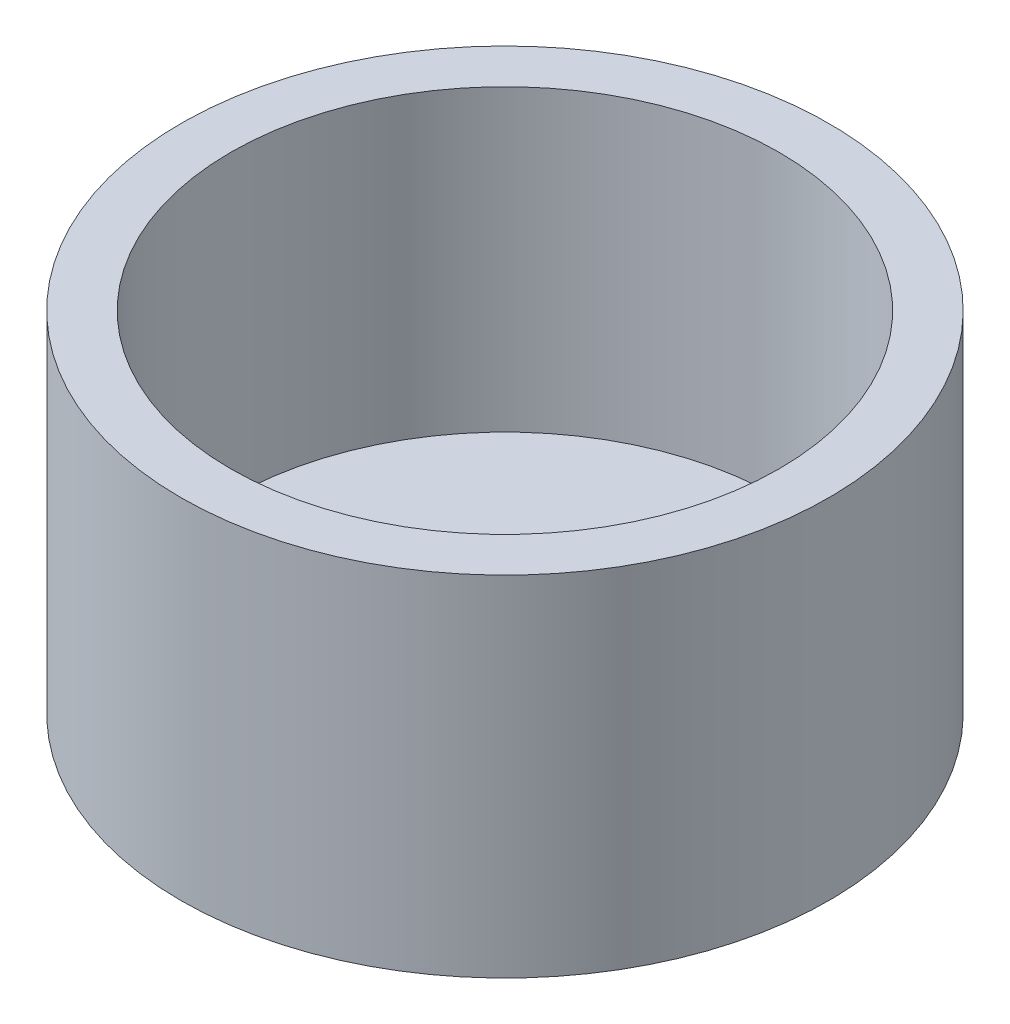
SolidWorks part; units mm, degrees
material "Polyether Polyol"
ref_plane "Front Plane" through (0, 0, 0) normal (0, 0, 1) x (1, 0, 0)
ref_plane "Top Plane" through (0, 0, 0) normal (0, 1, 0) x (1, 0, 0)
ref_plane "Right Plane" through (0, 0, 0) normal (1, 0, 0) x (0, 0, -1)
sketch "Sketch1" plane through (0, 0, 0) normal (0, 1, 0) x (1, 0, 0)
  circle A0 centre (0, 0) radius 165.1
  dimension "D1" = 330.2
extrude "Boss-Extrude1" add sketch "Sketch1" along normal blind 25.4
sketch "Sketch2" plane through (0, 25.4, 0) normal (0, 1, 0) x (1, 0, 0)
  circle A0 centre (0, 0) radius 165.1
  circle A1 centre (0, 0) radius 139.7
  dimension "D1" = 279.4
  dimension "D2" = 330.2
extrude "Boss-Extrude2" add sketch "Sketch2" along normal blind 152.4
